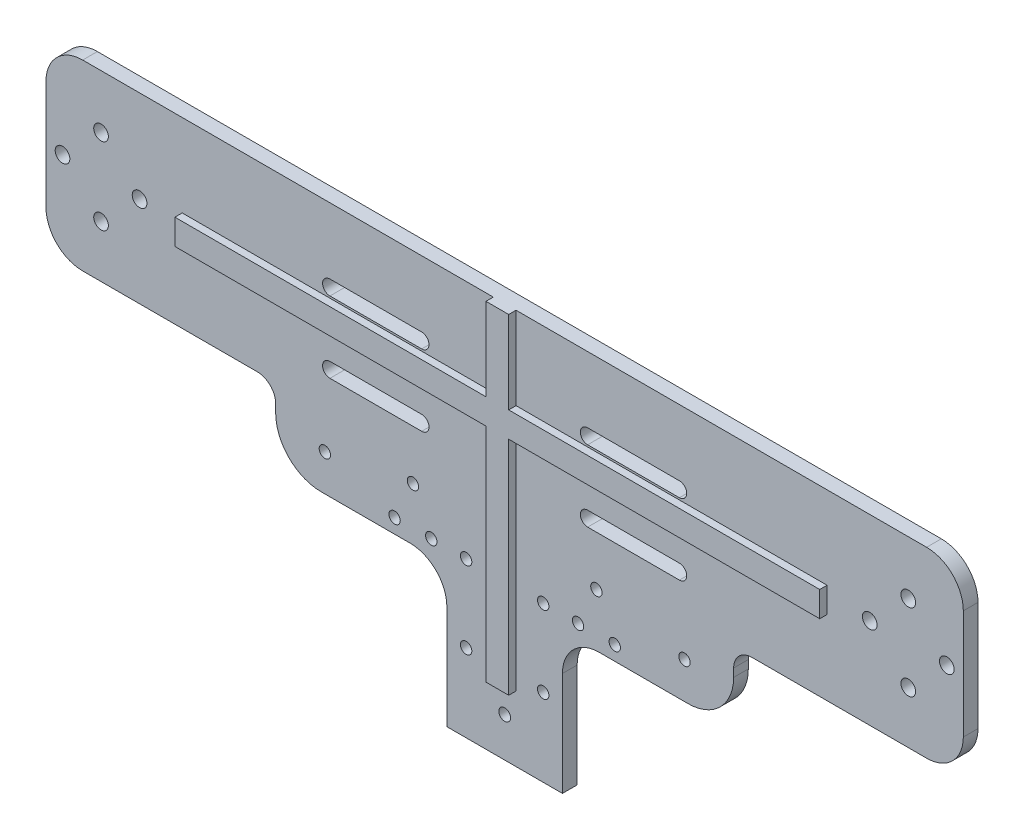
SolidWorks part; units mm, degrees
ref_plane "前视基准面" through (0, 0, 0) normal (0, 0, 1) x (1, 0, 0)
ref_plane "上视基准面" through (0, 0, 0) normal (0, 1, 0) x (1, 0, 0)
ref_plane "右视基准面" through (0, 0, 0) normal (1, 0, 0) x (0, 0, -1)
other "Configuration Table"
sketch "草图1" plane through (0, 0, 0) normal (0, 0, 1) x (1, 0, 0)
  line L0 (-67.4038, 4.4316) -> (-93.2578, 4.4316)
  line L6 (-5.4247, -11.2523) -> (-29.7322, -11.2523) construction
  line L7 (-24.7322, -0.7523) -> (0.2678, -0.7523) construction
  line L8 (-47.6193, 34.2239) -> (-22.6193, 34.2239) construction
  line L9 (-50, -15.1934) -> (-25.75, -15.1934)
  line L10 (-15.75, -25.1934) -> (-15.75, -53.5047)
  line L11 (-15.75, -53.5047) -> (15.75, -53.5047)
  line L12 (0, -53.5047) -> (0, 57.0384) construction
  line L13 (-62.4038, -2.7896) -> (-62.4038, -0.5684)
  line L14 (-95.5508, 54.2203) -> (95.5508, 54.2203)
  line L18 (-47.6193, 36.2239) -> (-22.6193, 36.2239)
  line L21 (-47.6193, 14.7886) -> (-22.6193, 14.7886) construction
  line L22 (-47.6193, 16.7886) -> (-22.6193, 16.7886)
  line L23 (-47.6193, 12.7886) -> (-22.6193, 12.7886)
  line L30 (115, 54.2203) -> (-115, 54.2203)
  line L32 (-115, 4.4316) -> (-93.2578, 4.4316)
  line L33 (47.6193, 14.7886) -> (22.6193, 14.7886) construction
  line L34 (47.6193, 16.7886) -> (22.6193, 16.7886)
  line L35 (47.6193, 12.7886) -> (22.6193, 12.7886)
  line L36 (24.7322, -0.7523) -> (-0.2678, -0.7523) construction
  line L37 (5.4247, -11.2523) -> (29.7322, -11.2523) construction
  line L38 (115, 4.4316) -> (93.2578, 4.4316)
  line L40 (62.4038, -2.7896) -> (62.4038, -0.5684)
  line L41 (15.75, -25.1934) -> (15.75, -53.5047)
  line L42 (50, -15.1934) -> (25.75, -15.1934)
  line L43 (67.4038, 4.4316) -> (93.2578, 4.4316)
  line L44 (-138.9752, 29.1264) -> (-61.5876, 29.1264) construction
  line L45 (-125, 44.2203) -> (-125, 14.4316)
  line L46 (125, 44.2203) -> (125, 14.4316)
  line L47 (-47.6193, 32.2239) -> (-22.6193, 32.2239)
  line L48 (-47.6193, 14.7886) -> (-47.6193, 50.832) construction
  line L49 (47.6193, 34.2239) -> (22.6193, 34.2239) construction
  line L50 (47.6193, 36.2239) -> (22.6193, 36.2239)
  line L51 (47.6193, 32.2239) -> (22.6193, 32.2239)
  arc A1 (0, -21.7489) -> (0.2678, -0.7523) centre (0.2678, -11.2523) cw construction
  circle A17 centre (-110, 29.1264) radius 10.5 construction
  circle A18 centre (-110, 39.6264) radius 2
  circle A19 centre (-99.5, 29.1264) radius 2
  circle A20 centre (-110, 18.6264) radius 2
  circle A21 centre (-120.5, 29.1264) radius 2
  arc A36 (-25.75, -15.1934) -> (-15.75, -25.1934) centre (-25.75, -25.1934) cw
  arc A39 (-50, -15.1934) -> (-62.4038, -2.7896) centre (-50, -2.7896) cw
  arc A43 (-67.4038, 4.4316) -> (-62.4038, -0.5684) centre (-67.4038, -0.5684) cw
  arc A46 (-47.6193, 16.7886) -> (-47.6193, 12.7886) centre (-47.6193, 14.7886) ccw
  arc A47 (-22.6193, 12.7886) -> (-22.6193, 16.7886) centre (-22.6193, 14.7886) ccw
  circle A52 centre (0, -42.7523) radius 1.6
  arc A53 (1.5953, -42.6304) -> (-1.5953, -42.6304) centre (0, -32.2523) cw construction
  arc A56 (47.6193, 16.7886) -> (47.6193, 12.7886) centre (47.6193, 14.7886) cw
  arc A57 (22.6193, 12.7886) -> (22.6193, 16.7886) centre (22.6193, 14.7886) cw
  circle A58 centre (110, 29.1264) radius 10.5 construction
  arc A59 (0, -21.7489) -> (-0.2678, -0.7523) centre (-0.2678, -11.2523) ccw construction
  arc A60 (67.4038, 4.4316) -> (62.4038, -0.5684) centre (67.4038, -0.5684) ccw
  arc A61 (50, -15.1934) -> (62.4038, -2.7896) centre (50, -2.7896) ccw
  arc A62 (25.75, -15.1934) -> (15.75, -25.1934) centre (25.75, -25.1934) ccw
  circle A63 centre (120.5, 29.1264) radius 2
  circle A64 centre (110, 18.6264) radius 2
  circle A65 centre (99.5, 29.1264) radius 2
  circle A66 centre (110, 39.6264) radius 2
  circle A77 centre (49, -5.2523) radius 1.55
  circle A78 centre (-10.5, -32.2523) radius 1.55
  circle A79 centre (0, -21.7489) radius 1.5466
  circle A80 centre (0, -0.7523) radius 1.55
  circle A81 centre (-49, -5.2523) radius 1.55
  circle A82 centre (-25, -0.7523) radius 1.55
  circle A83 centre (-30, -11.2523) radius 1.55
  circle A84 centre (-20, -11.2523) radius 1.55
  circle A85 centre (-10.5, -11.2523) radius 1.55
  circle A86 centre (30, -11.2523) radius 1.55
  circle A87 centre (20, -11.2523) radius 1.55
  circle A88 centre (25, -0.7523) radius 1.55
  circle A89 centre (10.5, -11.2523) radius 1.55
  circle A90 centre (10.5, -32.2523) radius 1.55
  arc A91 (-47.6193, 36.2239) -> (-47.6193, 32.2239) centre (-47.6193, 34.2239) ccw
  arc A92 (-22.6193, 32.2239) -> (-22.6193, 36.2239) centre (-22.6193, 34.2239) ccw
  arc A93 (47.6193, 36.2239) -> (47.6193, 32.2239) centre (47.6193, 34.2239) cw
  arc A94 (22.6193, 32.2239) -> (22.6193, 36.2239) centre (22.6193, 34.2239) cw
  arc A95 (125, 44.2203) -> (115, 54.2203) centre (115, 44.2203) ccw
  arc A96 (125, 14.4316) -> (115, 4.4316) centre (115, 14.4316) cw
  arc A97 (-125, 14.4316) -> (-115, 4.4316) centre (-115, 14.4316) ccw
  arc A98 (-125, 44.2203) -> (-115, 54.2203) centre (-115, 44.2203) cw
  point P2 (0, 54.2203)
  point P6 (-35.1193, 34.2239)
  point P15 (-35.1193, 14.7886)
  point P31 (35.1193, 34.2239)
  point P35 (35.1193, 14.7886)
  point P59 (0, 54.2203)
  point P98 (-62.4038, -0.4926)
  point P99 (0, 9.7477)
  point P102 (-34.7322, -0.2523)
  point P109 (0, 54.2203)
  point P115 (125, 54.2203)
  point P119 (0, 54.2203)
  point P120 (34.7322, -0.2523)
  point P121 (62.4038, -0.4926)
  point P124 (150, 4.4316)
  point P125 (125, 4.4316)
  point P127 (-150, 4.4316)
  point P130 (150, 54.2203)
  point P131 (-125, 4.4316)
  point P133 (-150, 54.2203)
  point P155 (-125, 54.2203)
  dimension "D1" = 21
  dimension "D2" = 4
  dimension "D3" = 10
  dimension "D4" = 4
  dimension "D5" = 220
  dimension "D9" = 3.2
  dimension "D8" = 25
  dimension "D10" = 125
  dimension "D11" = 28.3113
  dimension "D13" = 24.25
extrude "凸台-拉伸1" add sketch "草图1" along normal blind 4
sketch "草图2" plane through (0, 0, 4) normal (0, 0, 1) x (1, 0, 0)
  line L0 (0, 67.4496) -> (0, -73.2238) construction
  line L1 (3.0985, -35.6587) -> (-3.0985, -35.6587)
  line L2 (-3.0985, -35.6587) -> (-3.0985, 24.7818)
  line L3 (-3.0985, 54.2203) -> (3.0985, 54.2203)
  line L4 (115, 54.2203) -> (-115, 54.2203) construction
  line L5 (-3.0985, 31.6938) -> (-3.0985, 54.2203)
  line L6 (-87.8699, 31.6938) -> (-3.0985, 31.6938)
  line L7 (-87.8699, 31.6938) -> (-87.8699, 24.7818)
  line L8 (-87.8699, 24.7818) -> (-3.0985, 24.7818)
  line L10 (3.0985, 31.6938) -> (3.0985, 54.2203)
  line L11 (3.0985, -35.6587) -> (3.0985, 24.7818)
  line L12 (87.8699, 24.7818) -> (3.0985, 24.7818)
  line L13 (87.8699, 31.6938) -> (87.8699, 24.7818)
  line L14 (87.8699, 31.6938) -> (3.0985, 31.6938)
  point P9 (-59.2488, 28.2378)
  point P14 (0, -35.6587)
  point P15 (0, 54.2203)
extrude "凸台-拉伸2" add sketch "草图2" along normal blind 2
